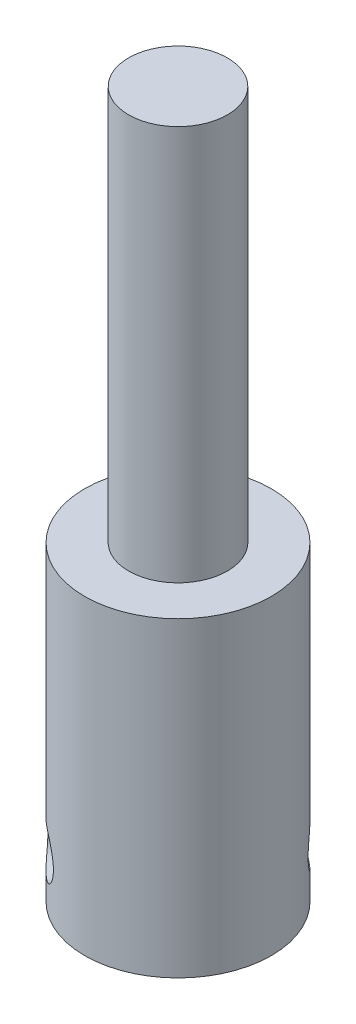
SolidWorks part; units mm, degrees
ref_plane "Front Plane" through (0, 0, 0) normal (0, 0, 1) x (1, 0, 0)
ref_plane "Top Plane" through (0, 0, 0) normal (0, 1, 0) x (1, 0, 0)
ref_plane "Right Plane" through (0, 0, 0) normal (1, 0, 0) x (0, 0, -1)
sketch "Sketch1" plane through (0, 0, 0) normal (0, 1, 0) x (1, 0, 0)
  circle A0 centre (0, 0) radius 6
  dimension "D1" = 12
extrude "Boss-Extrude1" add sketch "Sketch1" along normal blind 20
sketch "Sketch2" plane through (0, 20, 0) normal (0, 1, 0) x (1, 0, 0)
  circle A0 centre (0, 0) radius 3.175
  dimension "D1" = 6.35
extrude "Boss-Extrude2" add sketch "Sketch2" along normal blind 25.4
sketch "Sketch3" plane through (0, 45.4, 0) normal (0, 1, 0) x (1, 0, 0)
  circle A0 centre (0, 0) radius 2
extrude "Boss-Extrude3" [suppressed] add sketch "Sketch3" along normal blind 15
sketch "Sketch4" plane through (0, 0, 0) normal (0, -1, 0) x (-1, 0, 0)
  circle A0 centre (0, 0) radius 2.5
extrude "Cut-Extrude1" cut sketch "Sketch4" against normal blind 6.5
hole_wizard "Ø3.0mm Dowel Hole1" positions "3DSketch1" profile "Sketch5" hole size "Ø3.0" standard "ANSI Metric" end condition through all
sketch3d "3DSketch1"
  point P0 (-3.8743, 3.1748, 4.5815)
sketch "Sketch5" plane through (-3.8743, 3.1748, 4.5815) normal (0, 1, 0) x (0.7636, 0, 0.6457)
  line L0 (0, 0) -> (0, 14.4558)
  line L1 (0, 14.4558) -> (1.5, 14.4558)
  line L2 (1.5, 14.4558) -> (1.5, 0)
  line L5 (1.5, 0) -> (0, 0)
  line L11 (0, -6.35) -> (0, 107.95) construction
  dimension "Thru Hole Dia." = 3
  dimension "Thru Hole Depth" = 14.4558
